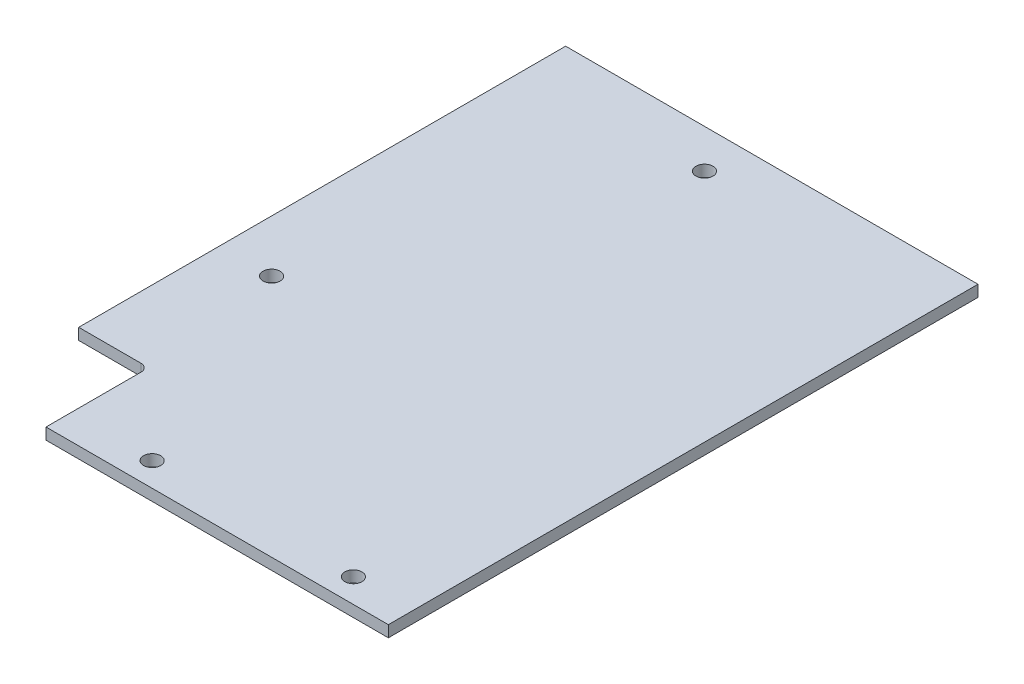
SolidWorks part; units mm, degrees
ref_plane "Front Plane" through (0, 0, 0) normal (0, 0, 1) x (1, 0, 0)
ref_plane "Top Plane" through (0, 0, 0) normal (0, 1, 0) x (1, 0, 0)
ref_plane "Right Plane" through (0, 0, 0) normal (1, 0, 0) x (0, 0, -1)
sketch "Sketch1" plane through (0, 0, 0) normal (0, 1, 0) x (1, 0, 0)
  line L0 (0, 0) -> (0, -155)
  line L1 (0, -155) -> (-90, -155)
  line L2 (-90, -155) -> (-90, -128)
  line L3 (-90, -128) -> (-108.4, -128)
  line L4 (-108.4, -128) -> (-108.4, 0)
  line L5 (-108.4, 0) -> (0, 0)
  dimension "D1" = 155
  dimension "D2" = 90
  dimension "D3" = 108.4
  dimension "D4" = 27
extrude "Boss-Extrude1" add sketch "Sketch1" along normal blind 3
sketch "Sketch2" plane through (0, 3, 0) normal (0, 1, 0) x (1, 0, 0)
  line L0 (-90, -155) -> (0, -155) construction
  line L1 (0, -155) -> (0, 0) construction
  line L2 (-108.4, 0) -> (-108.4, -128) construction
  circle A0 centre (-68.4, -148.7) radius 2.25
  circle A1 centre (-15.5, -148.7) radius 2.25
  circle A2 centre (-94.7, -91) radius 2.25
  circle A3 centre (-61.7, -10.2) radius 2.25
  dimension "D4" = 4.5
  dimension "D1" = 52.9
  dimension "D2" = 6.3
  dimension "D3" = 15.5
  dimension "D5" = 64
  dimension "D6" = 13.7
  dimension "D7" = 46.7
  dimension "D8" = 144.8
extrude "Cut-Extrude1" cut sketch "Sketch2" against normal through all
fillet "Fillet1" radius 2 1 edges at (-90, 1.5, 128)
